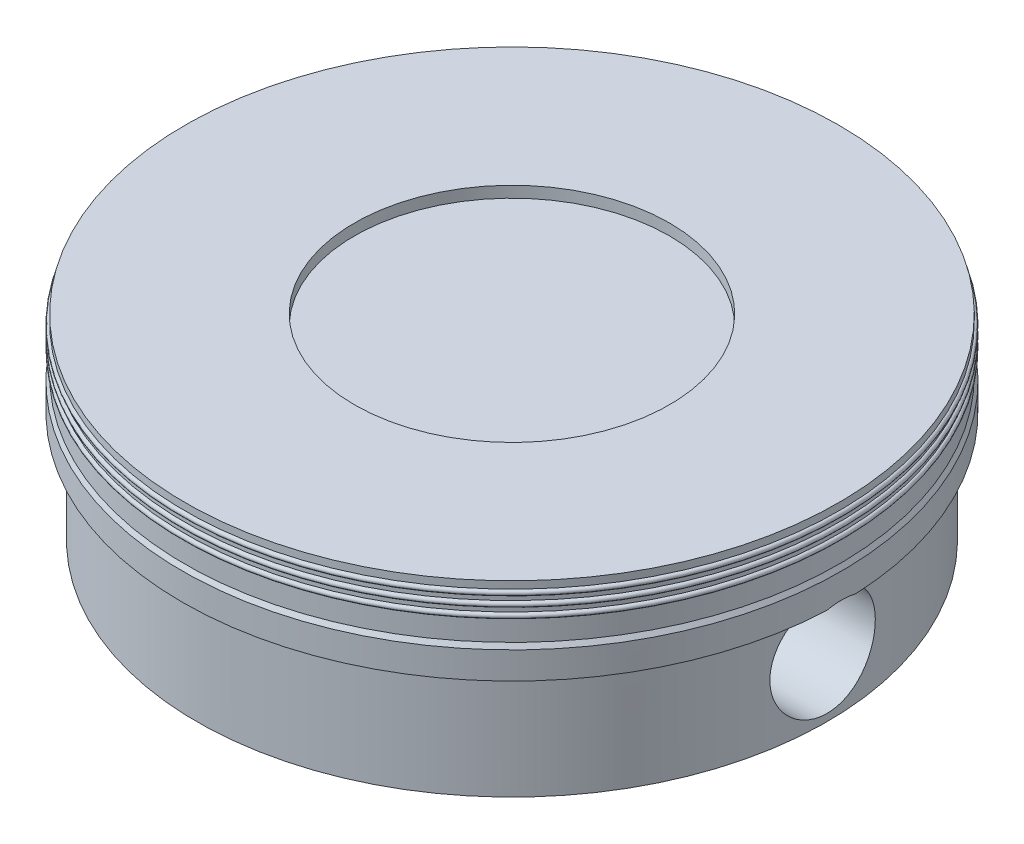
SolidWorks part; units mm, degrees
ref_plane "Front Plane" through (0, 0, 0) normal (0, 0, 1) x (1, 0, 0)
ref_plane "Top Plane" through (0, 0, 0) normal (0, 1, 0) x (1, 0, 0)
ref_plane "Right Plane" through (0, 0, 0) normal (1, 0, 0) x (0, 0, -1)
sketch "Sketch1" plane through (0, 0, 0) normal (0, 0, 1) x (1, 0, 0)
  line L0 (0, 0) -> (0, 3) construction
  line L1 (0, 0) -> (5, 0) construction
  line L3 (3.43, 1.93) -> (4.2, 1.93)
  line L4 (4.2, 1.93) -> (4.2, 2.33)
  line L5 (4.2, 2.33) -> (0, 2.33)
  line L6 (0, 2.33) -> (0, 2.8)
  line L7 (0, 2.8) -> (2.39, 2.8)
  line L8 (2.39, 2.8) -> (2.39, 2.97)
  line L9 (2.39, 2.97) -> (4.96, 2.97)
  line L10 (4.96, 2.97) -> (4.96, 2.86)
  line L13 (5, 1.68) -> (4.78, 1.68)
  line L16 (4.78, 1.68) -> (4.78, 0)
  line L17 (4.78, 0) -> (3.43, 0)
  line L18 (3.43, 0) -> (3.43, 1.93)
  line L19 (4.96, 2.16) -> (5, 2.09)
  line L20 (5, 2.09) -> (5, 1.68)
  line L21 (4.96, 2.78) -> (4.96, 2.71)
  line L22 (4.96, 2.63) -> (4.96, 2.56)
  line L23 (4.96, 2.48) -> (4.96, 2.16)
  arc A0 (4.96, 2.78) -> (4.96, 2.86) centre (4.96, 2.82) ccw
  arc A1 (4.96, 2.63) -> (4.96, 2.71) centre (4.96, 2.67) ccw
  arc A2 (4.96, 2.48) -> (4.96, 2.56) centre (4.96, 2.52) ccw
  dimension "D17" = 0.08
  dimension "D1" = 5
  dimension "D2" = 3
  dimension "D3" = 4.96
  dimension "D4" = 1.68
  dimension "D5" = 0.04
  dimension "D6" = 1.93
  dimension "D7" = 1.35
  dimension "D8" = 0.4
  dimension "D9" = 2.57
  dimension "D10" = 0.47
  dimension "D11" = 0.22
  dimension "D12" = 4.2
  dimension "D13" = 0.17
  dimension "D14" = 0.15
  dimension "D15" = 0.15
  dimension "D16" = 0.15
  dimension "D18" = 0.41
  dimension "D19" = 0.07
revolve "Revolve1" add sketch "Sketch1" angle 360 about L0
sketch "Sketch2" plane through (0, 0, 0) normal (0, -1, 0) x (1, 0, 0)
  line L0 (0, 0) -> (0, 3.43) construction
  line L1 (0, 0) -> (-3.43, 0) construction
  line L2 (-1.75, 2.95) -> (-1.75, -2.95)
  line L3 (1.75, 2.95) -> (1.75, -2.95)
  circle A0 centre (0, 0) radius 3.43 construction
  arc A1 (-1.75, 2.95) -> (-1.75, -2.95) centre (0, 0) ccw
  arc A2 (1.75, -2.95) -> (1.75, 2.95) centre (0, 0) ccw
  dimension "D1" = 3.5
extrude "Boss-Extrude1" add sketch "Sketch2" against normal up to next
sketch "Sketch3" plane through (0, 0, 0) normal (1, 0, 0) x (0, 0, -1)
  line L0 (-4.78, 0) -> (4.78, 0) construction
  circle A0 centre (0, 0.91) radius 0.8
  dimension "D1" = 1.6
  dimension "D2" = 0.91
extrude "Cut-Extrude1" cut sketch "Sketch3" against normal through all both and the other way through all
